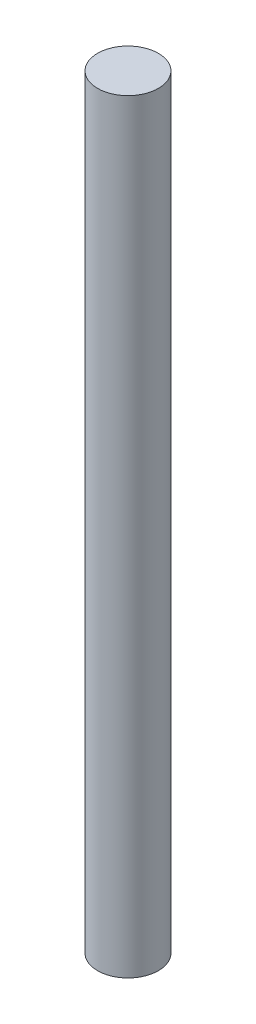
SolidWorks part; units mm, degrees
ref_plane "前视基准面" through (0, 0, 0) normal (0, 0, 1) x (1, 0, 0)
ref_plane "上视基准面" through (0, 0, 0) normal (0, 1, 0) x (1, 0, 0)
ref_plane "右视基准面" through (0, 0, 0) normal (1, 0, 0) x (0, 0, -1)
other "Configuration Table"
sketch "草图2" plane through (0, 0, 0) normal (0, 1, 0) x (1, 0, 0)
  circle A0 centre (0, 0) radius 1.99
  dimension "D1" = 3.98
extrude "凸台-拉伸3" add sketch "草图2" along normal blind 50
